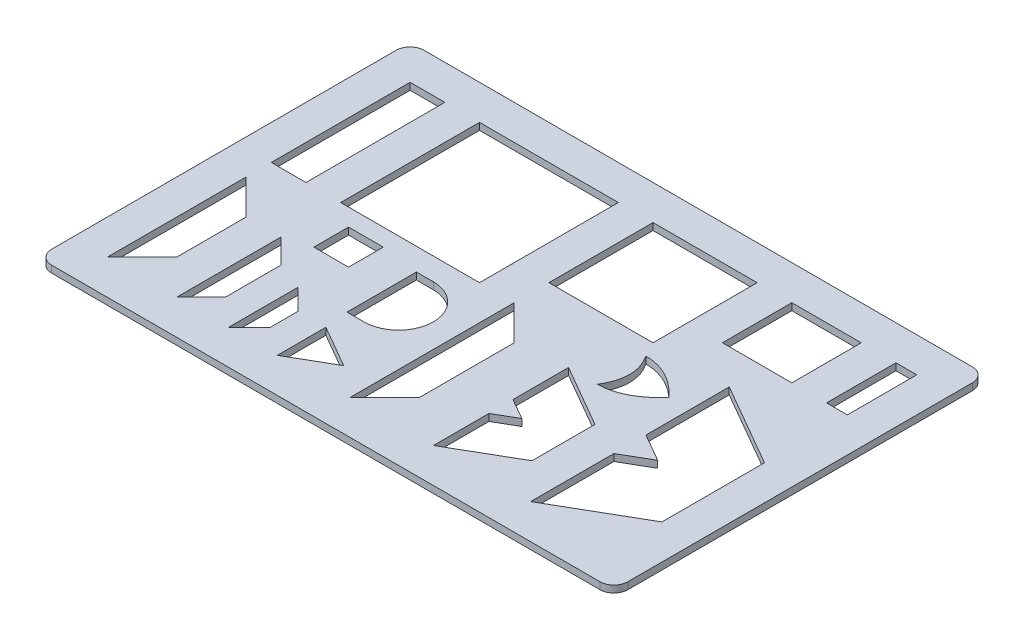
SolidWorks part; units mm, degrees
ref_plane "Front Plane" through (0, 0, 0) normal (0, 0, 1) x (1, 0, 0)
ref_plane "Top Plane" through (0, 0, 0) normal (0, 1, 0) x (1, 0, 0)
ref_plane "Right Plane" through (0, 0, 0) normal (1, 0, 0) x (0, 0, -1)
sketch "Sketch1" plane through (0, 0, 0) normal (0, 1, 0) x (1, 0, 0)
  line L0 (-62.2007, 5.0597) -> (-62.2007, -14.9403)
  line L1 (-52.2007, 28.6957) -> (-32.2007, 28.6957)
  line L2 (-52.2007, 28.6957) -> (-52.2007, 8.6957)
  line L3 (-52.2007, 8.6957) -> (-32.2007, 8.6957)
  line L4 (-32.2007, 28.6957) -> (-32.2007, 8.6957)
  line L5 (-52.2007, 28.6957) -> (-32.2007, 8.6957) construction
  line L6 (-52.2007, 8.6957) -> (-32.2007, 28.6957) construction
  line L7 (-27.2007, 28.6957) -> (-12.2007, 28.6957)
  line L8 (-27.2007, 28.6957) -> (-27.2007, 13.6957)
  line L9 (-27.2007, 13.6957) -> (-12.2007, 13.6957)
  line L10 (-12.2007, 28.6957) -> (-12.2007, 13.6957)
  line L11 (-27.2007, 28.6957) -> (-12.2007, 13.6957) construction
  line L12 (-27.2007, 13.6957) -> (-12.2007, 28.6957) construction
  line L13 (-7.2007, 28.6957) -> (2.7993, 28.6957)
  line L14 (-7.2007, 28.6957) -> (-7.2007, 18.6957)
  line L15 (-7.2007, 18.6957) -> (2.7993, 18.6957)
  line L16 (2.7993, 28.6957) -> (2.7993, 18.6957)
  line L17 (-7.2007, 28.6957) -> (2.7993, 18.6957) construction
  line L18 (-7.2007, 18.6957) -> (2.7993, 28.6957) construction
  line L19 (-62.2007, 28.6957) -> (-57.2007, 28.6957)
  line L20 (-62.2007, 28.6957) -> (-62.2007, 8.6957)
  line L21 (-62.2007, 8.6957) -> (-57.2007, 8.6957)
  line L22 (-57.2007, 28.6957) -> (-57.2007, 8.6957)
  line L23 (-62.2007, 28.6957) -> (-57.2007, 8.6957) construction
  line L24 (-62.2007, 8.6957) -> (-57.2007, 28.6957) construction
  line L25 (7.7993, 28.6957) -> (10.7993, 28.6957)
  line L26 (7.7993, 28.6957) -> (7.7993, 18.6957)
  line L27 (7.7993, 18.6957) -> (10.7993, 18.6957)
  line L28 (10.7993, 28.6957) -> (10.7993, 18.6957)
  line L29 (7.7993, 28.6957) -> (10.7993, 18.6957) construction
  line L30 (7.7993, 18.6957) -> (10.7993, 28.6957) construction
  line L31 (-62.2007, -14.9403) -> (-57.2007, -9.9403)
  line L32 (-57.2007, -9.9403) -> (-57.2007, 0.0597)
  line L33 (-57.2007, 0.0597) -> (-62.2007, 5.0597)
  line L34 (-52.2007, -14.9403) -> (-52.2007, 0.0597)
  line L35 (-52.2007, 0.0597) -> (-48.7007, -3.4403)
  line L36 (-48.7007, -3.4403) -> (-48.7007, -11.4403)
  line L37 (-48.7007, -11.4403) -> (-52.2007, -14.9403)
  line L38 (-44.7007, -4.9403) -> (-44.7007, -14.9403)
  line L39 (-44.7007, -14.9403) -> (-41.7007, -11.9403)
  line L40 (-41.7007, -11.9403) -> (-41.7007, -7.9403)
  line L41 (-44.7007, -4.9403) -> (-41.7007, -7.9403)
  line L42 (-1.2007, 13.6785) -> (-1.2007, 1.6785)
  line L43 (-1.2007, 1.6785) -> (2.7993, -0.6309)
  line L44 (2.7993, -0.6309) -> (-1.2007, -2.9403)
  line L45 (-1.2007, -2.9403) -> (-1.2007, -14.9403)
  line L46 (-1.2007, -14.9403) -> (10.7993, -8.0121)
  line L47 (10.7993, -8.0121) -> (10.7993, 6.7503)
  line L48 (10.7993, 6.7503) -> (-1.2007, 13.6785)
  line L49 (-15.2007, 4.5238) -> (-15.2007, -3.4762)
  line L50 (-15.2007, -3.4762) -> (-12.2007, -5.2083)
  line L51 (-12.2007, -5.2083) -> (-15.2007, -6.9403)
  line L52 (-15.2007, -6.9403) -> (-15.2007, -14.9403)
  line L53 (-15.2007, -14.9403) -> (-6.2007, -9.7442)
  line L54 (-6.2007, -9.7442) -> (-6.2007, -0.6724)
  line L55 (-6.2007, -0.6724) -> (-15.2007, 4.5238)
  line L56 (-27.2007, 8.6957) -> (-27.2007, -14.9403)
  line L57 (-27.2007, -14.9403) -> (-22.2007, -9.9403)
  line L58 (-22.2007, -9.9403) -> (-22.2007, 3.6957)
  line L59 (-22.2007, 3.6957) -> (-27.2007, 8.6957)
  line L60 (-37.7007, -14.9403) -> (-37.7007, -7.9403)
  line L61 (-48.5677, 6.1957) -> (-43.5677, 6.1957)
  line L62 (-48.5677, 6.1957) -> (-48.5677, 1.1957)
  line L63 (-48.5677, 1.1957) -> (-43.5677, 1.1957)
  line L64 (-43.5677, 6.1957) -> (-43.5677, 1.1957)
  line L65 (-48.5677, 6.1957) -> (-43.5677, 1.1957) construction
  line L66 (-48.5677, 1.1957) -> (-43.5677, 6.1957) construction
  line L67 (-37.7007, -7.9403) -> (-31.6385, -11.4403)
  line L68 (-31.6385, -11.4403) -> (-37.7007, -14.9403)
  line L69 (-35.6343, 5.4785) -> (-38.0738, 5.4785)
  line L70 (-38.0738, 5.4785) -> (-38.0738, -4.5215)
  line L71 (-38.0738, -4.5215) -> (-35.6343, -4.5215)
  line L72 (-11.0419, 11.5179) -> (-8.8092, 8.0179) construction
  line L73 (-67.2007, 33.6957) -> (15.7993, 33.6957)
  line L74 (-67.2007, 33.6957) -> (-67.2007, -19.9403)
  line L75 (-67.2007, -19.9403) -> (15.7993, -19.9403)
  line L76 (15.7993, 33.6957) -> (15.7993, -19.9403)
  line L77 (-8.8092, 8.0179) -> (-11.0419, 4.5179) construction
  line L78 (-11.0419, 11.5179) -> (-7.4532, 11.5179) construction
  line L79 (-7.4532, 11.5179) -> (-4.2014, 8.0179) construction
  line L80 (-11.0419, 4.5179) -> (-7.4041, 4.5179) construction
  line L81 (-7.4041, 4.5179) -> (-4.2014, 8.0179) construction
  arc A0 (-35.6343, -4.5215) -> (-35.6343, 5.4785) centre (-35.6343, 0.4785) ccw
  spline S0 degree 2 poles (-11.0419, 11.5179) (-8.8092, 8.0179) (-11.0419, 4.5179) knots 0 0 0 1 1 1
  spline S1 degree 2 poles (-11.0419, 11.5179) (-7.4532, 11.5179) (-4.2014, 8.0179) knots 0 0 0 1 1 1
  spline S2 degree 2 poles (-11.0419, 4.5179) (-7.4041, 4.5179) (-4.2014, 8.0179) knots 0 0 0 1 1 1
  point P0 (-42.2007, 18.6957)
  point P5 (-19.7007, 21.1957)
  point P10 (-2.2007, 23.6957)
  point P15 (-59.7007, 18.6957)
  point P20 (9.2993, 23.6957)
  point P55 (-46.0677, 3.6957)
  point P78 (-12.5832, 8.2608)
  point P79 (-8.8092, 7.3743)
  point P80 (-4.2014, 7.6734)
  dimension "D50" = 10
  dimension "D1" = 20
  dimension "D2" = 20
  dimension "D3" = 15
  dimension "D4" = 15
  dimension "D5" = 10
  dimension "D6" = 10
  dimension "D7" = 20
  dimension "D8" = 5
  dimension "D9" = 10
  dimension "D10" = 3
  dimension "D11" = 0
  dimension "D12" = 0
  dimension "D13" = 0
  dimension "D14" = 0
  dimension "D15" = 5
  dimension "D16" = 5
  dimension "D17" = 5
  dimension "D18" = 5
  dimension "D19" = 20
  dimension "D20" = 45
  dimension "D21" = 45
  dimension "D22" = 15
  dimension "D23" = 45
  dimension "D24" = 45
  dimension "D25" = 3.5
  dimension "D26" = 10
  dimension "D27" = 45
  dimension "D28" = 45
  dimension "D29" = 3
  dimension "D30" = 0
  dimension "D31" = 4
  dimension "D32" = 12
  dimension "D33" = 12
  dimension "D34" = 4
  dimension "D35" = 0
  dimension "D36" = 0
  dimension "D37" = 12
  dimension "D38" = 120
  dimension "D39" = 120
  dimension "D40" = 4
  dimension "D41" = 0
  dimension "D42" = 8
  dimension "D43" = 8
  dimension "D44" = 3
  dimension "D45" = 0
  dimension "D46" = 9
  dimension "D47" = 0
  dimension "D48" = 120
  dimension "D49" = 120
  dimension "D51" = 5
  dimension "D52" = 45
  dimension "D53" = 45
  dimension "D54" = 5
  dimension "D55" = 5
  dimension "D56" = 5
  dimension "D57" = 7
  dimension "D58" = 7
  dimension "D59" = 0
  dimension "D60" = 0
  dimension "D61" = 7
  dimension "D62" = 0
  dimension "D63" = 0
  dimension "D64" = 7
  dimension "D65" = 5
  dimension "D66" = 5
  dimension "D67" = 5
  dimension "D68" = 5
  dimension "D69" = 3.5
extrude "Boss-Extrude1" add sketch "Sketch1" along normal blind 1
fillet "Fillet1" radius 2 4 edges at (-67.2007, 0.5, 19.9403) (-67.2007, 0.5, -33.6957) (15.7993, 0.5, -33.6957) (15.7993, 0.5, 19.9403)
